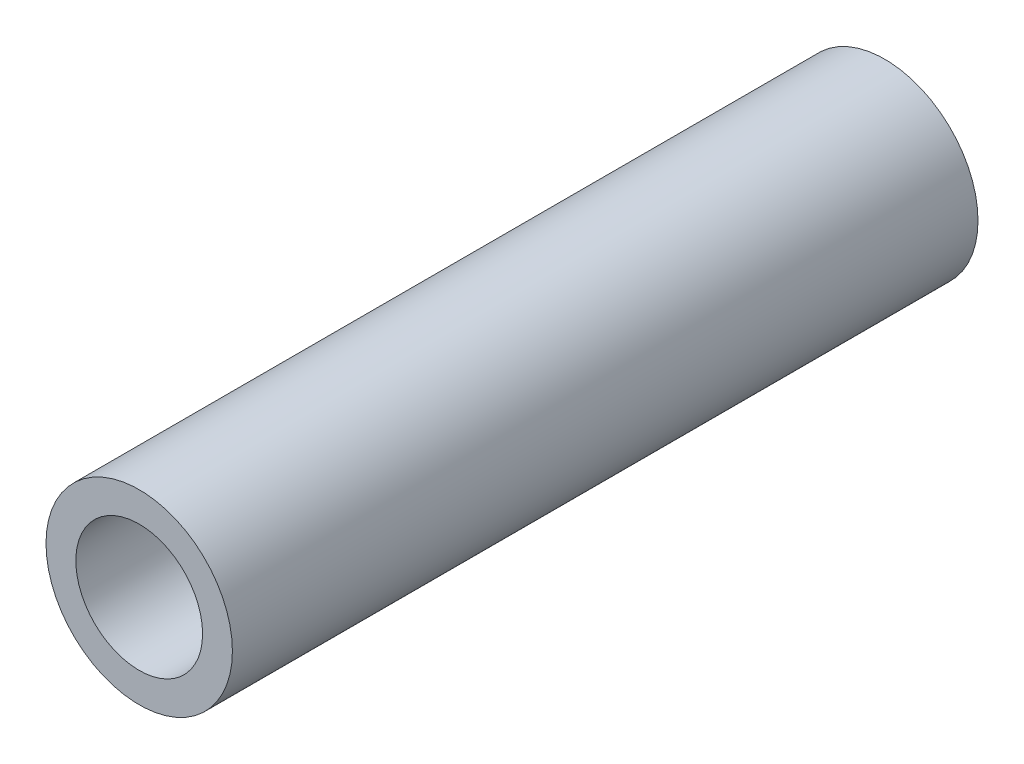
SolidWorks part; units mm, degrees
ref_plane "Front Plane" through (0, 0, 0) normal (1, 0, 0) x (0, 1, 0)
ref_plane "Top Plane" through (0, 0, 0) normal (0, 0, 1) x (0, 1, 0)
ref_plane "Right Plane" through (0, 0, 0) normal (0, 1, 0) x (-1, 0, 0)
sketch "Sketch1" plane through (0, 0, 0) normal (0, 0, 1) x (0, 1, 0)
  circle A0 centre (0, 0) radius 2.5
  dimension "D1" = 5
extrude "Boss-Extrude1" add sketch "Sketch1" along normal blind 20
sketch "Sketch2" plane through (0, 0, 20) normal (0, 0, 1) x (1, 0, 0)
  circle A0 centre (0, 0) radius 1.7
  dimension "D1" = 3.4
extrude "Cut-Extrude1" cut sketch "Sketch2" against normal through all both and the other way through all
